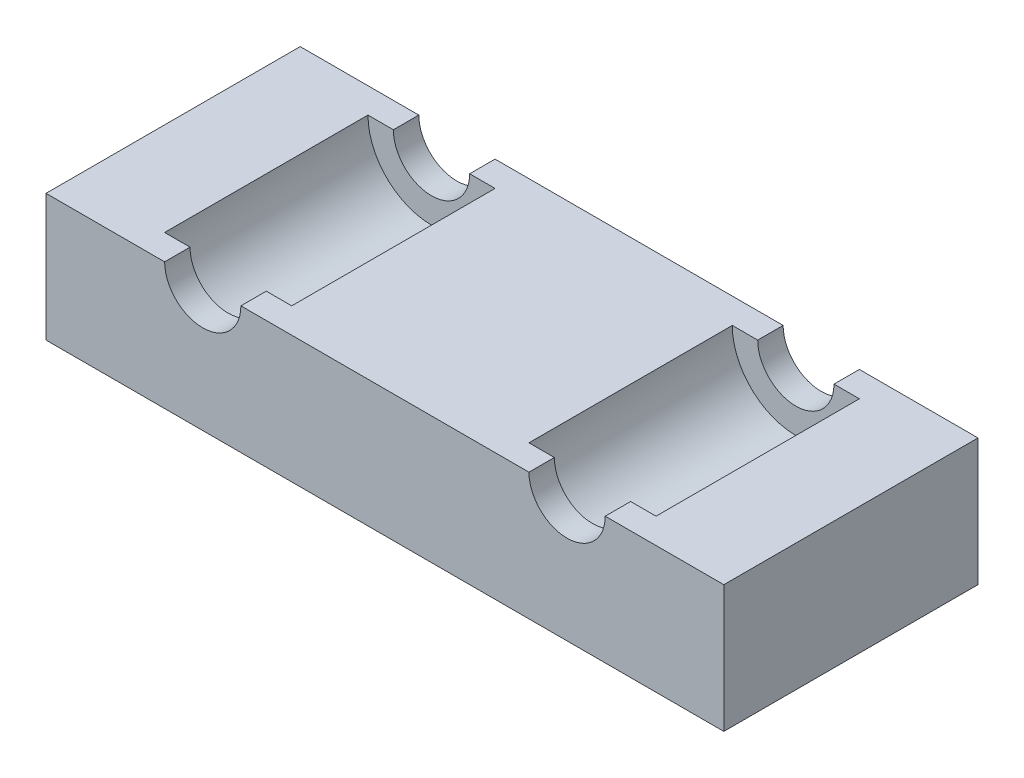
SolidWorks part; units mm, degrees
ref_plane "Front Plane" through (0, 0, 0) normal (0, 0, 1) x (1, 0, 0)
ref_plane "Top Plane" through (0, 0, 0) normal (0, 1, 0) x (1, 0, 0)
ref_plane "Right Plane" through (0, 0, 0) normal (1, 0, 0) x (0, 0, -1)
sketch "Sketch1" plane through (0, 0, 0) normal (0, 1, 0) x (1, 0, 0)
  line L1 (0, 0) -> (80, 0)
  line L2 (0, 0) -> (0, 30)
  line L3 (0, 30) -> (80, 30)
  line L4 (80, 0) -> (80, 30)
  dimension "D1" = 80
  dimension "D2" = 30
extrude "Boss-Extrude1" add sketch "Sketch1" along normal blind 15
sketch "Sketch2" plane through (0, 0, 0) normal (0, 0, 1) x (1, 0, 0)
  line L0 (0, 15) -> (80, 15) construction
  line L1 (0, 15) -> (0, 0) construction
  circle A0 centre (18.5, 15) radius 7.5
  circle A1 centre (61.5, 15) radius 7.5
  dimension "D1" = 15
  dimension "D2" = 15
  dimension "D3" = 43
  dimension "D4" = 18.5
extrude "Cut-Extrude1" cut sketch "Sketch2" against normal through all
sketch "Sketch3" plane through (0, 15, 0) normal (0, 1, 0) x (1, 0, 0)
  line L0 (11, 15) -> (69, 15) construction
  line L1 (11, 0) -> (11, 30) construction
  line L2 (69, 30) -> (69, 0) construction
  line L3 (26, 30) -> (26, 0) construction
  line L4 (11, 0) -> (26, 0)
  line L5 (11, 0) -> (11, 3)
  line L6 (11, 3) -> (26, 3)
  line L7 (26, 0) -> (26, 3)
  line L8 (69, 30) -> (69, 27)
  line L9 (54, 0) -> (69, 0)
  line L10 (54, 0) -> (54, 3)
  line L11 (54, 3) -> (69, 3)
  line L12 (69, 0) -> (69, 3)
  line L13 (54, 27) -> (69, 27)
  line L14 (54, 30) -> (54, 27)
  line L15 (54, 30) -> (69, 30)
  line L16 (26, 30) -> (26, 27)
  line L17 (11, 27) -> (26, 27)
  line L18 (11, 30) -> (11, 27)
  line L19 (11, 30) -> (26, 30)
  dimension "D1" = 3
  dimension "D2" = 3
extrude "Boss-Extrude2" add sketch "Sketch3" against normal blind 10
sketch "Sketch4" plane through (0, 0, 0) normal (0, 0, 1) x (1, 0, 0)
  line L0 (0, 15) -> (80, 15) construction
  line L1 (0, 15) -> (0, 0) construction
  circle A0 centre (18.5, 15) radius 4.5
  circle A1 centre (61.5, 15) radius 4.5
  dimension "D1" = 9
  dimension "D2" = 9
  dimension "D3" = 43
  dimension "D4" = 18.5
extrude "Cut-Extrude2" cut sketch "Sketch4" against normal through all both and the other way through all
